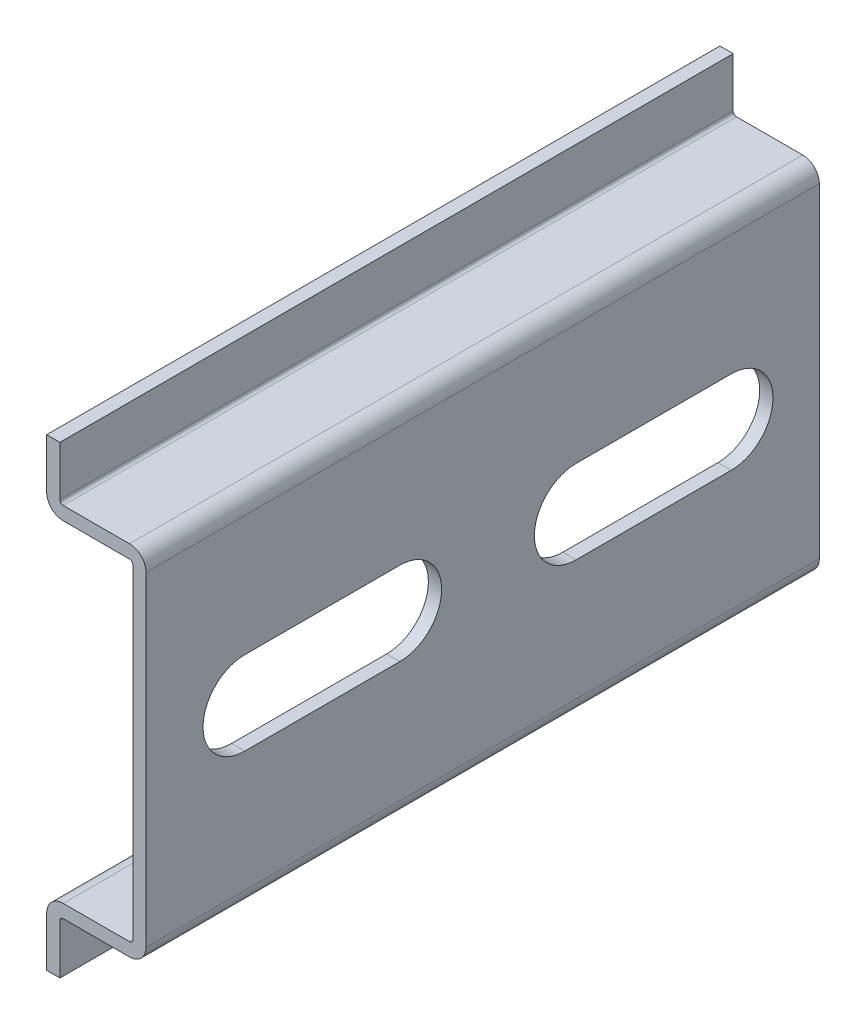
SolidWorks part; units mm, degrees
ref_plane "Front Plane" through (0, 0, 0) normal (0, 0, 1) x (1, 0, 0)
ref_plane "Top Plane" through (0, 0, 0) normal (0, 1, 0) x (1, 0, 0)
ref_plane "Right Plane" through (0, 0, 0) normal (1, 0, 0) x (0, 0, -1)
sketch "Sketch1" plane through (0, 0, 0) normal (0, 0, 1) x (1, 0, 0)
  line L0 (0, -13.5) -> (0, 13.5) construction
  line L1 (0, 13.5) -> (-6.5, 13.5) construction
  line L2 (-6.5, 13.5) -> (-6.5, 17.5) construction
  line L3 (0, -13.5) -> (-6.5, -13.5) construction
  line L4 (-6.5, -13.5) -> (-6.5, -17.5) construction
  line L5 (-7.5, 0) -> (0, 0) construction
  line L6 (-6.5, 17.5) -> (-7.5, 17.5) construction
  line L7 (-7.5, 0) -> (-7.5, 17.5) construction
  dimension "D1" = 27
  dimension "Height" = 35
  dimension "Depth" = 7.5
  dimension "Metal Thickness" = 1
sketch "Sketch2" plane through (0, 0, 0) normal (1, 0, 0) x (0, 0, -1)
  line L0 (0, 0) -> (-50.8, 0) construction
  line L1 (-6.35, 17.5) -> (-6.35, -17.5) construction
  line L2 (-44.45, 17.5) -> (-44.45, -17.5) construction
  line L3 (-6.35, 17.5) -> (-44.45, 17.5) construction
  line L4 (-25.4, 0) -> (-25.4, 17.5) construction
  point P8 (-44.45, 0)
  point P9 (-6.35, 0)
  dimension "Length" = 50.8
  dimension "D1" = 38.1
sketch "Sketch3" plane through (0, 0, 0) normal (0, 0, 1) x (1, 0, 0)
  line L0 (-6.5, -13.5) -> (-6.5, -17.5) construction
  line L1 (0, -13.5) -> (-6.5, -13.5) construction
  line L2 (0, -13.5) -> (0, 13.5) construction
  line L3 (0, 13.5) -> (-6.5, 13.5) construction
  line L4 (-6.5, 13.5) -> (-6.5, 17.5) construction
  line L5 (-6.5, -13.5) -> (-6.5, -17.5)
  line L6 (0, -13.5) -> (-6.5, -13.5)
  line L7 (0, -13.5) -> (0, 13.5)
  line L8 (0, 13.5) -> (-6.5, 13.5)
  line L9 (-6.5, 13.5) -> (-6.5, 17.5)
extrude "Extrude-Thin1" add sketch "Sketch3" along normal up to vertex (50.8 mm away) thin
sketch "Sketch4" plane through (0, 0, 0) normal (1, 0, 0) x (0, 0, -1)
  line L0 (0, 0) -> (-62.1077, 0) construction
  line L1 (-6.65, 0) -> (-18.35, 0) construction
  line L2 (-6.65, -3.15) -> (-18.35, -3.15)
  line L3 (-6.65, 3.15) -> (-18.35, 3.15)
  arc A0 (-6.65, -3.15) -> (-6.65, 3.15) centre (-6.65, 0) ccw
  arc A1 (-18.35, 3.15) -> (-18.35, -3.15) centre (-18.35, 0) ccw
  point P5 (-12.5, 0)
  point P10 (-3.5, 0)
  point P11 (-21.5, 0)
  point P12 (-37.5, 0)
  dimension "D1" = 18
  dimension "Mounting Hole Diameter" = 6.3
  dimension "D3" = 12.5
  dimension "Mounting Hole C to C" = 25
extrude "Cut-Extrude1" cut sketch "Sketch4" against normal through all both and the other way through all
pattern_linear "LPattern1" count 2 spacing 25 along (0, 0, 1) of "Cut-Extrude1"
fillet "Fillet1" radius 0.25 4 edges at (-6.5, 13.5, 25.4) (-6.5, -13.5, 25.4) (-1, 12.5, 25.4) (-1, -12.5, 25.4)
fillet "Fillet2" radius 1.25 4 edges at (-7.5, -12.5, 25.4) (0, -13.5, 25.4) (0, 13.5, 25.4) (-7.5, 12.5, 25.4)
ref_plane "Contact Plane 1" through (-1, 0, 0) normal (-1, 0, 0) x (0, 0, 1)
equation "\"D3@LPattern1\" = \"Mounting Hole C to C@Sketch4\""
equation "\"D1@LPattern1\"=\"Length@Sketch2\" / \"D3@LPattern1\""
equation "\"D5@Extrude-Thin1\"=\"Metal Thickness@Sketch1\""
equation "\"D3@Sketch4\"=\"Mounting Hole C to C@Sketch4\"/2"
equation "\"D1@Sketch2\"=\"Length@Sketch2\"*.75"
